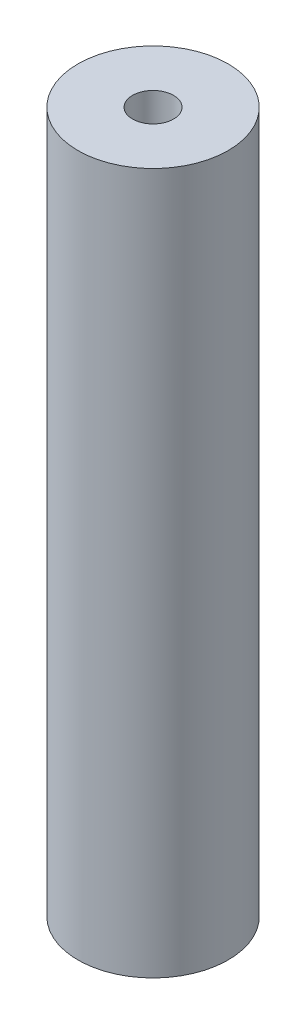
SolidWorks part; units mm, degrees
ref_plane "Front Plane" through (0, 0, 0) normal (0, 0, 1) x (1, 0, 0)
ref_plane "Top Plane" through (0, 0, 0) normal (0, 1, 0) x (1, 0, 0)
ref_plane "Right Plane" through (0, 0, 0) normal (1, 0, 0) x (0, 0, -1)
ref_plane "Plane1"
sketch "Sketch1" plane through (0, 0, 0) normal (0, 1, 0) x (-1, 0, 0)
  circle A0 centre (0, 0) radius 7.5
  dimension "D1" = 15
extrude "Extrusion1" add sketch "Sketch1" along normal blind 160
sketch "Sketch2" plane through (0, 160, 0) normal (0, 1, 0) x (-1, 0, 0)
  circle A0 centre (0, 0) radius 2.25
  dimension "D1" = 4.5
extrude "Extrusion2" cut sketch "Sketch2" against normal blind 80
ref_plane "Plane2"
sketch "Sketch4" plane through (0, 0, 0) normal (0, -1, 0) x (1, 0, 0)
  circle A0 centre (0, 0) radius 9.9883
extrude "Extrusion4" cut sketch "Sketch4" against normal blind 45
sketch "Sketch5" plane through (0, 45, 0) normal (0, -1, 0) x (1, 0, 0)
  circle A0 centre (0, 0) radius 7.5
  circle A1 centre (0, 0) radius 4
  circle M1 centre (0, 0) radius 7.5
  dimension "D1" = 15
extrude "Extrusion5" cut sketch "Sketch5" against normal blind 15 contours A1 M1
sketch "Sketch6" plane through (0, 45, 0) normal (0, -1, 0) x (1, 0, 0)
  circle A0 centre (0, 0) radius 13.0014
extrude "Cut-Extrude1" cut sketch "Sketch6" against normal blind 45 contours A0
sketch "Sketch7" plane through (0, 90, 0) normal (0, -1, 0) x (1, 0, 0)
  circle A0 centre (0, 0) radius 2.05
  circle A1 centre (0, 0) radius 2.25 construction
  circle A2 centre (0, 0) radius 4.6393
  dimension "D1" = 0.2
extrude "Boss-Extrude1" add sketch "Sketch7" against normal up to surface (70 mm away) up to face at (0, 160, 2.25)
